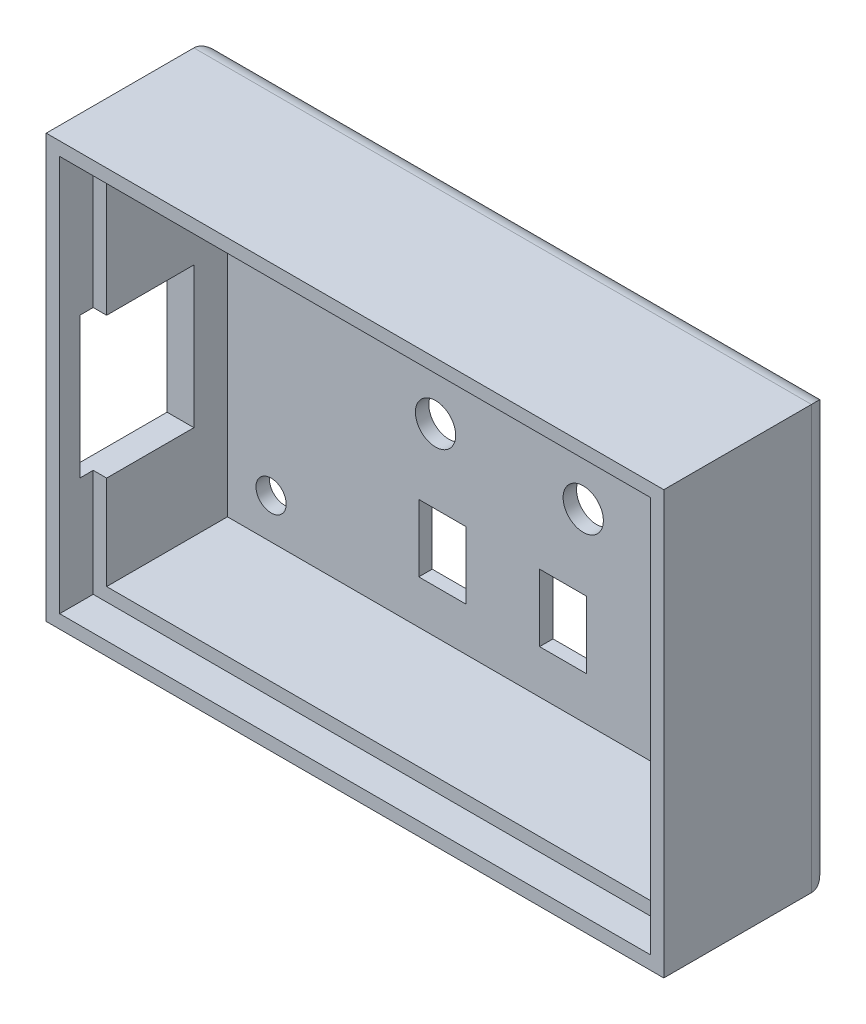
SolidWorks part; units mm, degrees
ref_plane "Front Plane" through (0, 0, 0) normal (0, 0, 1) x (1, 0, 0)
ref_plane "Top Plane" through (0, 0, 0) normal (0, 1, 0) x (1, 0, 0)
ref_plane "Right Plane" through (0, 0, 0) normal (1, 0, 0) x (0, 0, -1)
sketch "Sketch3" plane through (0, 0, 0) normal (0, 0, 1) x (1, 0, 0)
  line L1 (0, 0) -> (92, 0)
  line L2 (0, 0) -> (0, 63)
  line L3 (0, 63) -> (92, 63)
  line L4 (92, 0) -> (92, 63)
  line L5 (8, 55.5) -> (84.5, 55.5)
  line L6 (8, 55.5) -> (8, 7.5)
  line L7 (8, 7.5) -> (84.5, 7.5)
  line L8 (84.5, 55.5) -> (84.5, 7.5)
  line L29 (75, 20.5) -> (68, 20.5)
  line L30 (75, 20.5) -> (75, 10.5)
  line L31 (75, 10.5) -> (68, 10.5)
  line L32 (68, 20.5) -> (68, 10.5)
  line L33 (57.5, 20.5) -> (50.5, 20.5)
  line L34 (57.5, 20.5) -> (57.5, 10.5)
  line L35 (57.5, 10.5) -> (50.5, 10.5)
  line L36 (50.5, 20.5) -> (50.5, 10.5)
  line L37 (39.5, 20.5) -> (32.5, 20.5)
  line L38 (39.5, 20.5) -> (39.5, 10.5)
  line L39 (39.5, 10.5) -> (32.5, 10.5)
  line L40 (32.5, 20.5) -> (32.5, 10.5)
  circle A1 centre (35, 31.5) radius 3
  circle A2 centre (57, 31.5) radius 3
  circle A3 centre (77, 31.5) radius 3
  circle A4 centre (82, 53) radius 2.25
  circle A5 centre (82, 10) radius 2.25
  circle A6 centre (10.5, 10) radius 2.25
  circle A7 centre (10.5, 53) radius 2.25
  point P40 (50.5, 15.5)
  dimension "D12" = 6
  dimension "D13" = 6
  dimension "D14" = 6
  dimension "D23" = 4.5
  dimension "D24" = 4.5
  dimension "D25" = 4.5
  dimension "D26" = 4.5
  dimension "D1" = 63
  dimension "D2" = 92
  dimension "D3" = 48
  dimension "D4" = 76.5
  dimension "D5" = 7.5
  dimension "D6" = 8
  dimension "D7" = 7.5
  dimension "D8" = 7.5
  dimension "D9" = 22
  dimension "D10" = 20
  dimension "D15" = 24
  dimension "D16" = 24
  dimension "D17" = 24
  dimension "D19" = 9.5
  dimension "D20" = 7
  dimension "D22" = 10
  dimension "D27" = 2.5
  dimension "D28" = 2.5
  dimension "D29" = 2.5
  dimension "D30" = 2.5
  dimension "D31" = 2.5
  dimension "D32" = 2.5
  dimension "D33" = 2.5
  dimension "D34" = 2.5
  dimension "D35" = 10.5
  dimension "D36" = 7
  dimension "D37" = 5
  dimension "D38" = 3
  dimension "D39" = 3
  dimension "D40" = 11
  dimension "D41" = 7
  dimension "D42" = 3
  dimension "D43" = 10
extrude "Boss-Extrude3" add sketch "Sketch3" along normal blind 25
sketch "Sketch4" plane through (0, 0, 25) normal (0, 0, 1) x (1, 0, 0)
  line L0 (0, 0) -> (0, 63) construction
  line L1 (4, 59) -> (88, 59)
  line L2 (4, 59) -> (4, 4)
  line L3 (4, 4) -> (88, 4)
  line L4 (88, 59) -> (88, 4)
  line L5 (0, 0) -> (92, 0) construction
  line L6 (0, 63) -> (92, 63) construction
  line L7 (92, 0) -> (92, 63) construction
  dimension "D1" = 4
  dimension "D2" = 4
  dimension "D3" = 4
  dimension "D4" = 4
extrude "Cut-Extrude1" cut sketch "Sketch4" against normal blind 23
sketch "Sketch5" plane through (0, 0, 25) normal (0, 0, 1) x (1, 0, 0)
  line L0 (0, 0) -> (0, 63) construction
  line L1 (2, 61) -> (90, 61)
  line L2 (2, 61) -> (2, 2)
  line L3 (2, 2) -> (90, 2)
  line L4 (90, 61) -> (90, 2)
  line L5 (0, 63) -> (92, 63) construction
  line L6 (92, 0) -> (92, 63) construction
  line L7 (0, 0) -> (92, 0) construction
  dimension "D1" = 2
  dimension "D2" = 2
  dimension "D3" = 2
  dimension "D4" = 2
extrude "Cut-Extrude2" cut sketch "Sketch5" against normal blind 5
fillet "Fillet1" radius 3 4 edges at (46, 0, 0) (0, 31.5, 0) (46, 63, 0) (92, 31.5, 0)
sketch "Sketch6" plane through (0, 0, 0) normal (-1, 0, 0) x (0, 0, 1)
  line L0 (25, 0) -> (3, 0) construction
  line L1 (22, 18) -> (7, 18)
  line L2 (22, 18) -> (22, 39)
  line L3 (22, 39) -> (7, 39)
  line L4 (7, 18) -> (7, 39)
  line L5 (25, 0) -> (25, 63) construction
  dimension "D1" = 18
  dimension "D2" = 21
  dimension "D3" = 15
  dimension "D4" = 3
extrude "Cut-Extrude3" cut sketch "Sketch6" against normal blind 5
